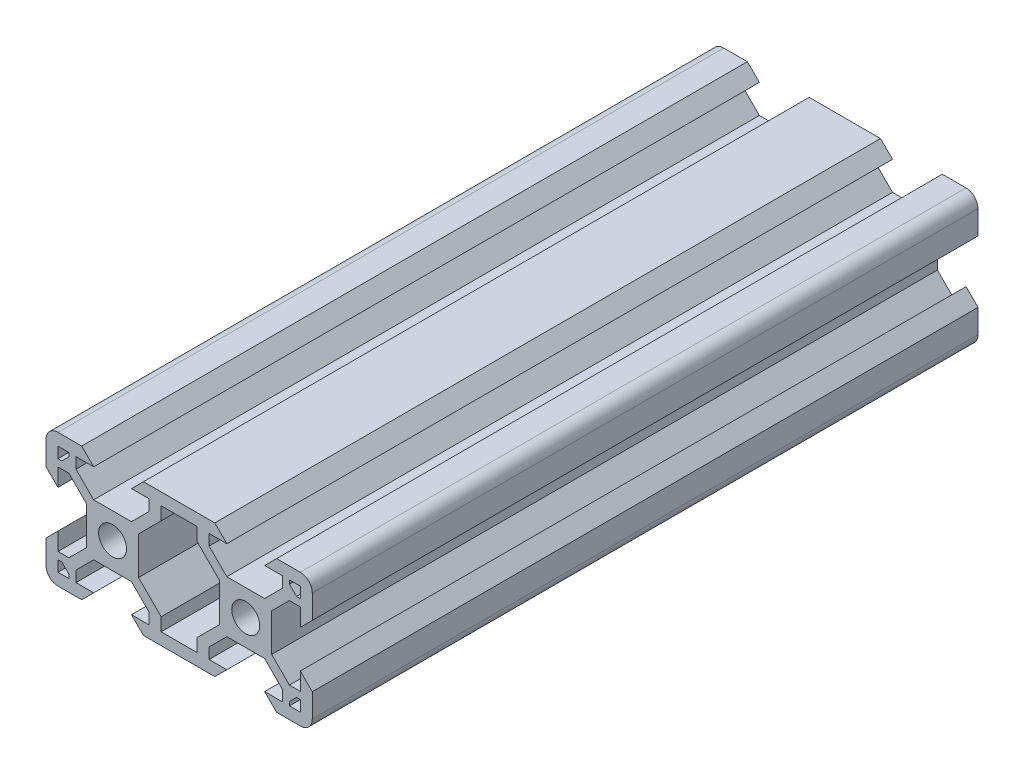
SolidWorks part; units mm, degrees
material "5052-H38, Barre (SS)"
ref_plane "Plan de face" through (0, 0, 0) normal (0, 0, 1) x (1, 0, 0)
ref_plane "Plan de dessus" through (0, 0, 0) normal (0, 1, 0) x (1, 0, 0)
ref_plane "Plan de droite" through (0, 0, 0) normal (1, 0, 0) x (0, 0, -1)
sketch "Esquisse1" plane through (0, 0, 0) normal (0, 0, 1) x (1, 0, 0)
  line L0 (0, 0) -> (0, 10) construction
  line L1 (0, 0) -> (-20, 0) construction
  line L2 (-10, 0) -> (-20, 10) construction
  line L3 (-10, 3.9007) -> (-12.84, 3.9007)
  line L4 (-12.84, 3.9007) -> (-15.4993, 6.56)
  line L5 (-15.4993, 6.56) -> (-15.4993, 8.2)
  line L6 (-15.4993, 8.2) -> (-12.84, 8.2)
  line L7 (-12.84, 8.2) -> (-14.64, 10)
  line L8 (-14.64, 10) -> (-18.2, 10)
  line L9 (-10, 0) -> (-10, 10) construction
  line L10 (-20, 4.64) -> (-20, 8.2)
  line L11 (-18.2, 2.84) -> (-20, 4.64)
  line L12 (-18.2, 5.4993) -> (-18.2, 2.84)
  line L13 (-16.56, 5.4993) -> (-18.2, 5.4993)
  line L14 (-13.9007, 2.84) -> (-16.56, 5.4993)
  line L15 (-13.9007, 0) -> (-13.9007, 2.84)
  line L16 (-10, -3.9007) -> (-12.84, -3.9007)
  line L17 (-12.84, -3.9007) -> (-15.4993, -6.56)
  line L18 (-15.4993, -6.56) -> (-15.4993, -8.2)
  line L19 (-15.4993, -8.2) -> (-12.84, -8.2)
  line L20 (-12.84, -8.2) -> (-14.64, -10)
  line L21 (-14.64, -10) -> (-18.2, -10)
  line L22 (-20, -4.64) -> (-20, -8.2)
  line L23 (-18.2, -2.84) -> (-20, -4.64)
  line L24 (-18.2, -5.4993) -> (-18.2, -2.84)
  line L25 (-16.56, -5.4993) -> (-18.2, -5.4993)
  line L26 (-13.9007, -2.84) -> (-16.56, -5.4993)
  line L27 (-13.9007, 0) -> (-13.9007, -2.84)
  line L28 (-10, 0) -> (0, 10) construction
  line L29 (-10, 3.9007) -> (-7.16, 3.9007)
  line L30 (-7.16, 3.9007) -> (-4.5007, 6.56)
  line L31 (-4.5007, 6.56) -> (-4.5007, 8.2)
  line L32 (-4.5007, 8.2) -> (-7.16, 8.2)
  line L33 (-7.16, 8.2) -> (-5.36, 10)
  line L34 (-7.16, -8.2) -> (-5.36, -10)
  line L35 (-4.5007, -8.2) -> (-7.16, -8.2)
  line L36 (-4.5007, -6.56) -> (-4.5007, -8.2)
  line L37 (-7.16, -3.9007) -> (-4.5007, -6.56)
  line L38 (-10, -3.9007) -> (-7.16, -3.9007)
  line L39 (-5.36, 10) -> (5.36, 10)
  line L40 (-5.36, -10) -> (5.36, -10)
  line L41 (-2.7, 8.2) -> (-2.7, 6.2393)
  line L42 (-2.7, 6.2393) -> (-6.0993, 2.84)
  line L43 (-2.7, 8.2) -> (2.7, 8.2)
  line L44 (-6.0993, 2.84) -> (-6.0993, -2.84)
  line L45 (-7.16, 3.9007) -> (-6.0993, 2.84) construction
  line L46 (-2.7, -8.2) -> (2.7, -8.2)
  line L47 (-2.7, -8.2) -> (-2.7, -6.2393)
  line L48 (-2.7, -6.2393) -> (-6.0993, -2.84)
  line L49 (-18.2, 8.2) -> (-18.2, 6.5693)
  line L50 (-18.2, 6.5693) -> (-17.63, 6.5693)
  line L51 (-17.63, 6.5693) -> (-16.5693, 7.63)
  line L52 (-16.5693, 7.63) -> (-16.5693, 8.2)
  line L53 (-16.5693, 8.2) -> (-18.2, 8.2)
  line L54 (-18.2, -6.5693) -> (-17.63, -6.5693)
  line L55 (-18.2, -8.2) -> (-18.2, -6.5693)
  line L56 (-16.5693, -8.2) -> (-18.2, -8.2)
  line L57 (-16.5693, -7.63) -> (-16.5693, -8.2)
  line L58 (-17.63, -6.5693) -> (-16.5693, -7.63)
  line L59 (18.2, 6.5693) -> (17.63, 6.5693)
  line L60 (18.2, 8.2) -> (18.2, 6.5693)
  line L61 (16.5693, 8.2) -> (18.2, 8.2)
  line L62 (16.5693, 7.63) -> (16.5693, 8.2)
  line L63 (17.63, 6.5693) -> (16.5693, 7.63)
  line L64 (18.2, -6.5693) -> (17.63, -6.5693)
  line L65 (18.2, -8.2) -> (18.2, -6.5693)
  line L66 (16.5693, -8.2) -> (18.2, -8.2)
  line L67 (16.5693, -7.63) -> (16.5693, -8.2)
  line L68 (17.63, -6.5693) -> (16.5693, -7.63)
  line L69 (2.7, 8.2) -> (2.7, 6.2393)
  line L70 (2.7, 6.2393) -> (6.0993, 2.84)
  line L71 (6.0993, 2.84) -> (6.0993, -2.84)
  line L72 (2.7, -6.2393) -> (6.0993, -2.84)
  line L73 (2.7, -8.2) -> (2.7, -6.2393)
  line L74 (7.16, -8.2) -> (5.36, -10)
  line L75 (4.5007, -8.2) -> (7.16, -8.2)
  line L76 (4.5007, -6.56) -> (4.5007, -8.2)
  line L77 (7.16, -3.9007) -> (4.5007, -6.56)
  line L78 (10, -3.9007) -> (7.16, -3.9007)
  line L79 (10, -3.9007) -> (12.84, -3.9007)
  line L80 (12.84, -3.9007) -> (15.4993, -6.56)
  line L81 (15.4993, -6.56) -> (15.4993, -8.2)
  line L82 (15.4993, -8.2) -> (12.84, -8.2)
  line L83 (12.84, -8.2) -> (14.64, -10)
  line L84 (14.64, -10) -> (18.2, -10)
  line L85 (20, -4.64) -> (20, -8.2)
  line L86 (18.2, -2.84) -> (20, -4.64)
  line L87 (18.2, -5.4993) -> (18.2, -2.84)
  line L88 (16.56, -5.4993) -> (18.2, -5.4993)
  line L89 (13.9007, -2.84) -> (16.56, -5.4993)
  line L90 (13.9007, 0) -> (13.9007, -2.84)
  line L91 (13.9007, 0) -> (13.9007, 2.84)
  line L92 (13.9007, 2.84) -> (16.56, 5.4993)
  line L93 (16.56, 5.4993) -> (18.2, 5.4993)
  line L94 (18.2, 5.4993) -> (18.2, 2.84)
  line L95 (18.2, 2.84) -> (20, 4.64)
  line L96 (20, 4.64) -> (20, 8.2)
  line L97 (14.64, 10) -> (18.2, 10)
  line L98 (12.84, 8.2) -> (14.64, 10)
  line L99 (15.4993, 8.2) -> (12.84, 8.2)
  line L100 (15.4993, 6.56) -> (15.4993, 8.2)
  line L101 (12.84, 3.9007) -> (15.4993, 6.56)
  line L102 (10, 3.9007) -> (12.84, 3.9007)
  line L103 (10, 3.9007) -> (7.16, 3.9007)
  line L104 (7.16, 3.9007) -> (4.5007, 6.56)
  line L105 (4.5007, 6.56) -> (4.5007, 8.2)
  line L106 (4.5007, 8.2) -> (7.16, 8.2)
  line L107 (7.16, 8.2) -> (5.36, 10)
  circle A0 centre (-10, 0) radius 2.1
  arc A1 (-18.2, 10) -> (-20, 8.2) centre (-18.2, 8.2) ccw
  arc A2 (-20, -8.2) -> (-18.2, -10) centre (-18.2, -8.2) ccw
  circle A3 centre (10, 0) radius 2.1
  arc A4 (20, -8.2) -> (18.2, -10) centre (18.2, -8.2) cw
  arc A5 (18.2, 10) -> (20, 8.2) centre (18.2, 8.2) cw
  point P57 (-6.0993, 0)
  point P61 (-17.0997, 7.0997)
  point P80 (0, 8.2)
  point P85 (0, -8.2)
  point P86 (0, -10)
  dimension "D3" = 4.2
  dimension "D2" = 20
  dimension "D4" = 5.68
  dimension "D5" = 1.5
  dimension "D6" = 1.8
  dimension "D7" = 1.64
  dimension "D11" = 5.4
  dimension "D12" = 1.07
  dimension "D8" = 2
  dimension "D9" = 2
  dimension "D10" = 2
extrude "Boss.-Extru.1" add sketch "Esquisse1" along normal mid plane 100
